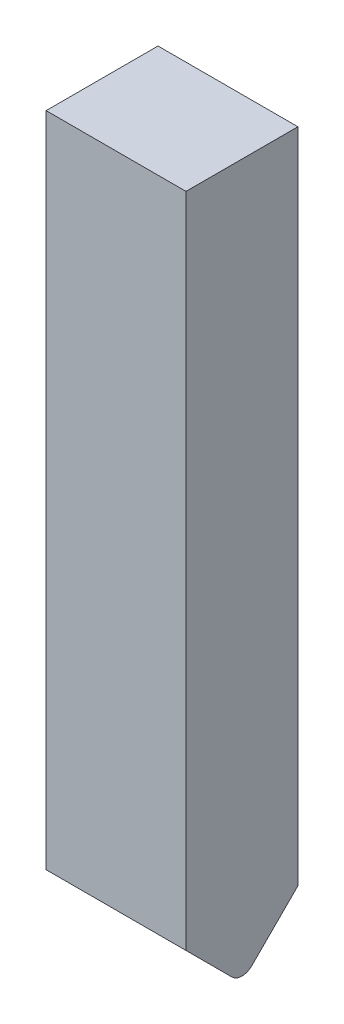
SolidWorks part; units mm, degrees
ref_plane "Front Plane" through (0, 0, 0) normal (0, 0, 1) x (1, 0, 0)
ref_plane "Top Plane" through (0, 0, 0) normal (0, 1, 0) x (1, 0, 0)
ref_plane "Right Plane" through (0, 0, 0) normal (1, 0, 0) x (0, 0, -1)
sketch "Sketch1" plane through (0, 0, 0) normal (1, 0, 0) x (0, 0, -1)
  line L0 (-10.16, 0) -> (-10.16, -119.38)
  line L1 (10.16, 0) -> (10.16, -119.38)
  line L2 (-10.16, -119.38) -> (0, -129.54)
  line L3 (0, -129.54) -> (10.16, -119.38)
  line L4 (-10.16, 0) -> (10.16, 0)
  line L5 (0, -129.54) -> (0, 0) construction
  point P6 (0, 0)
  dimension "D1" = 90
  dimension "D2" = 119.38
  dimension "D4" = 20.32
extrude "Boss-Extrude1" add sketch "Sketch1" along normal blind 25.4
fillet "Fillet1" radius 2.54 1 edges at (12.7, -129.54, 0)
